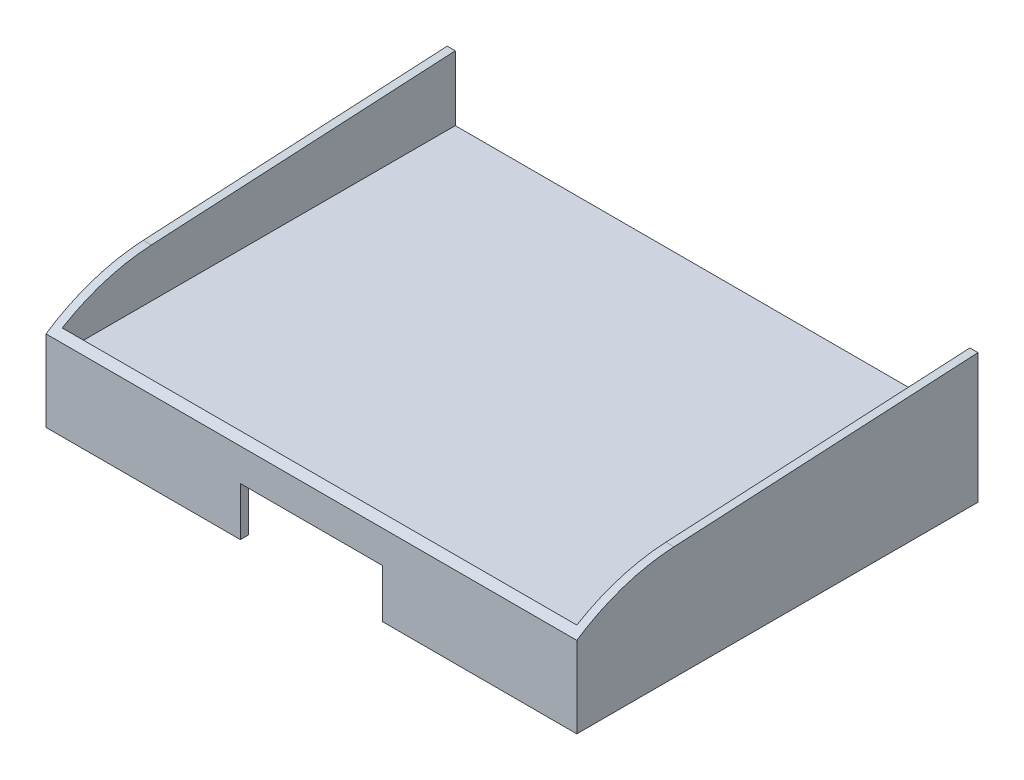
SolidWorks part; units mm, degrees
material "Custom Plastic"
ref_plane "Front Plane" through (0, 0, 0) normal (0, 0, 1) x (1, 0, 0)
ref_plane "Top Plane" through (0, 0, 0) normal (0, 1, 0) x (1, 0, 0)
ref_plane "Right Plane" through (0, 0, 0) normal (1, 0, 0) x (0, 0, -1)
sketch "Sketch1" plane through (0, 0, 0) normal (0, 1, 0) x (1, 0, 0)
  line L15 (-167.513, -142.113) -> (248.567, -142.113)
  line L16 (-167.513, -142.113) -> (-167.513, 172.367)
  line L17 (-167.513, 172.367) -> (248.567, 172.367)
  line L18 (248.567, -142.113) -> (248.567, 172.367)
extrude "Boss-Extrude2" add sketch "Sketch1" along normal blind 101.6
sketch "Sketch2" plane through (0, 101.6, 0) normal (0, 1, 0) x (1, 0, 0)
  line L0 (-167.513, -142.113) -> (248.567, -142.113) construction
  line L1 (-161.163, -135.763) -> (242.217, -135.763)
  line L2 (-161.163, -135.763) -> (-161.163, 172.367)
  line L3 (-161.163, 172.367) -> (242.217, 172.367)
  line L4 (242.217, -135.763) -> (242.217, 172.367)
  line L5 (-167.513, 172.367) -> (-167.513, -142.113) construction
  line L6 (248.567, -142.113) -> (248.567, 172.367) construction
  line L7 (248.567, 172.367) -> (-167.513, 172.367) construction
  point P0 (238.5537, 163.2014)
  point P6 (0, 0)
  dimension "D1" = 6.35
  dimension "D2" = 6.35
  dimension "D3" = 6.35
  dimension "D4" = 0
extrude "Cut-Extrude1" cut sketch "Sketch2" against normal through all
sketch "Sketch3" plane through (248.567, 0, 0) normal (1, 0, 0) x (0, 0, -1)
  line L5 (-142.113, 63.5) -> (-142.113, 101.6)
  line L6 (-142.113, 101.6) -> (-142.113, 0) construction
  line L7 (-142.113, 101.6) -> (172.367, 101.6)
  line L8 (172.367, 101.6) -> (-65.913, 88.9)
  arc A1 (-65.913, 88.9) -> (-142.113, 63.5) centre (-57.8558, -62.2717) ccw
  dimension "D1" = 38.1
  dimension "D2" = 12.7
  dimension "D3" = 76.2
extrude "Cut-Extrude2" cut sketch "Sketch3" against normal through all contours L5 L7 L8 A1
sketch "Sketch4" plane through (0, 0, 142.113) normal (0, 0, 1) x (1, 0, 0)
  line L0 (-167.513, 0) -> (248.567, 0) construction
  line L1 (96.167, 0) -> (-15.113, 0)
  line L2 (96.167, 0) -> (96.167, 38.1)
  line L3 (96.167, 38.1) -> (-15.113, 38.1)
  line L4 (-15.113, 0) -> (-15.113, 38.1)
  line L6 (248.567, 63.5) -> (248.567, 0) construction
  line L7 (-167.513, 63.5) -> (-167.513, 0) construction
  dimension "D1" = 152.4
  dimension "D2" = 152.4
  dimension "D3" = 38.1
extrude "Cut-Extrude3" cut sketch "Sketch4" against normal up to next
sketch "Sketch5" plane through (0, 0, 135.763) normal (0, 0, -1) x (-1, 0, 0)
  line L0 (161.163, 0) -> (161.163, 101.6) construction
  line L1 (-242.217, 50.8) -> (161.163, 50.8)
  line L2 (-242.217, 50.8) -> (-242.217, 38.1)
  line L3 (-242.217, 38.1) -> (161.163, 38.1)
  line L4 (161.163, 50.8) -> (161.163, 38.1)
  dimension "D1" = 12.7
extrude "Boss-Extrude3" add sketch "Sketch5" along normal up to surface (308.13 mm away)
